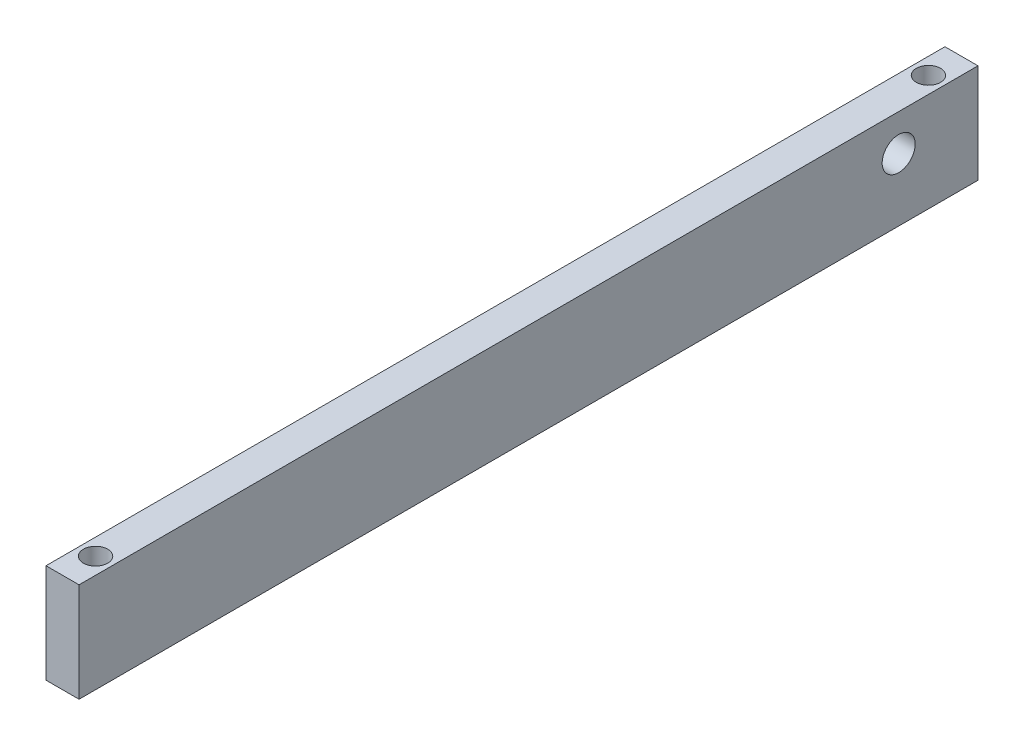
SolidWorks part; units mm, degrees
other "Markup1"
sketch "Sketch6" plane through (0, 0, 0) normal (0.1266, -0.8901, -0.4379) x (-0.2811, -0.4555, 0.8447)
ref_plane "Front Plane" through (0, 0, 0) normal (0, 0, 1) x (1, 0, 0)
ref_plane "Top Plane" through (0, 0, 0) normal (0, 1, 0) x (1, 0, 0)
ref_plane "Right Plane" through (0, 0, 0) normal (1, 0, 0) x (0, 0, -1)
sketch "Sketch1" plane through (0, 0, 0) normal (0, 0, 1) x (1, 0, 0)
  line L0 (0, 0) -> (-6.35, 0)
  line L3 (-6.35, 0) -> (-6.35, 19.05)
  line L4 (-6.35, 19.05) -> (0, 19.05)
  line L5 (0, 19.05) -> (0, 0)
  dimension "D1" = 19.05
  dimension "D4" = 6.35
extrude "Boss-Extrude1" add sketch "Sketch1" along normal blind 172.72
sketch "Sketch2" plane through (0, 19.05, 0) normal (0, 1, 0) x (1, 0, 0)
  line L0 (-3.175, 0) -> (-3.175, -172.72) construction
  line L3 (-6.35, 0) -> (0, 0) construction
  line L4 (-6.35, -172.72) -> (0, -172.72) construction
  circle A0 centre (-3.175, -166.37) radius 2.3368
  circle A1 centre (-3.175, -6.35) radius 2.3368
  dimension "D1" = 4.6736
  dimension "D2" = 6.35
  dimension "D3" = 6.35
sketch "Sketch3" plane through (0, 0, 0) normal (0, -1, 0) x (1, 0, 0)
  line L0 (-3.175, 0) -> (-3.175, 172.72) construction
  line L3 (0, 172.72) -> (0, 0) construction
  line L4 (0, 0) -> (-6.35, 0) construction
  line L5 (0, 172.72) -> (-6.35, 172.72) construction
  circle A0 centre (-3.175, 166.37) radius 2.54
  circle A1 centre (-3.175, 6.35) radius 2.54
  dimension "D2" = 5.08
  dimension "D1" = 3.175
  dimension "D3" = 6.35
  dimension "D4" = 6.35
sketch "Sketch4" plane through (0, 0, 0) normal (1, 0, 0) x (0, 0, -1)
  line L0 (0, 19.05) -> (0, 0) construction
  line L3 (-172.72, 19.05) -> (0, 19.05) construction
  circle A0 centre (-15.24, 12.065) radius 3.175
  dimension "D3" = 6.35
  dimension "D1" = 15.24
  dimension "D2" = 6.985
extrude "Cut-Extrude3" cut sketch "Sketch4" against normal blind 25.4
sketch "Sketch5" plane through (0, 0, 172.72) normal (0, 0, 1) x (1, 0, 0)
  line L1 (-6.35, 0) -> (-12.7, 0)
  line L2 (-6.35, 0) -> (-6.35, 6.35)
  line L3 (-6.35, 6.35) -> (-12.7, 6.35)
  line L4 (-12.7, 0) -> (-12.7, 6.35)
  dimension "D1" = 6.35
  dimension "D2" = 6.35
extrude "Cut-Extrude4" cut sketch "Sketch2" against normal through all
